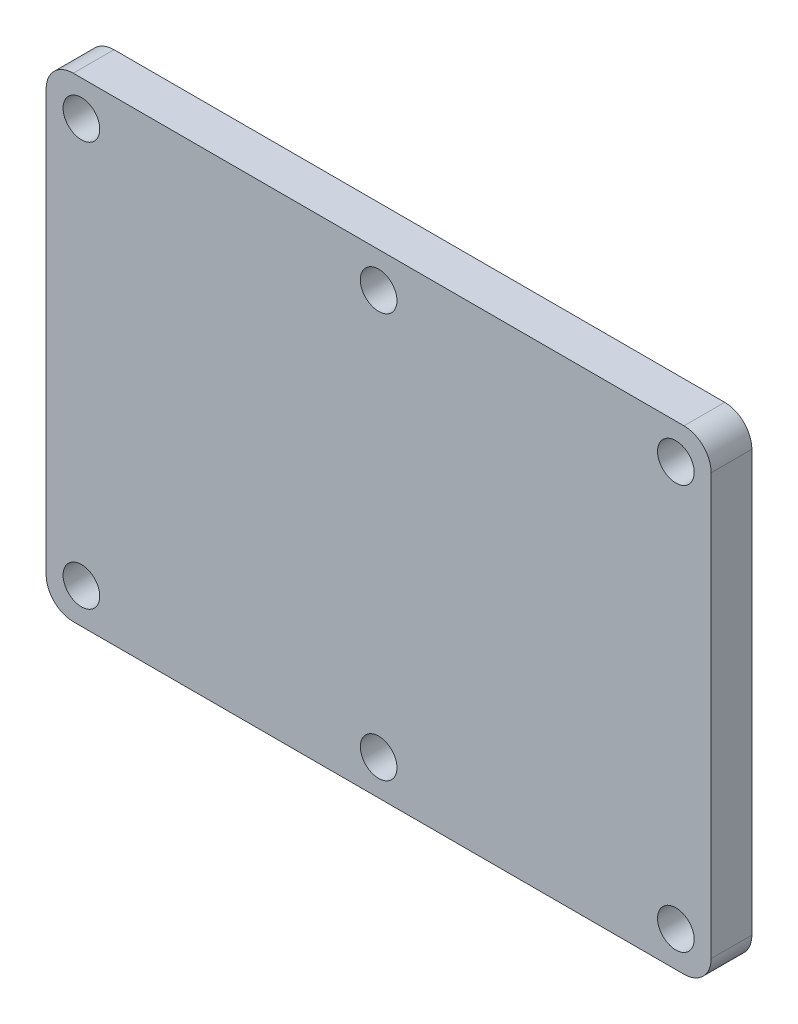
SolidWorks part; units mm, degrees
ref_plane "Plano frontal" through (0, 0, 0) normal (0, 0, 1) x (1, 0, 0)
ref_plane "Plano superior" through (0, 0, 0) normal (0, 1, 0) x (1, 0, 0)
ref_plane "Plano direito" through (0, 0, 0) normal (1, 0, 0) x (0, 0, -1)
sketch "Esboço1" plane through (0, 0, 0) normal (0, 0, 1) x (1, 0, 0)
  line L1 (-24.5, 17.5) -> (24.5, 17.5)
  line L2 (-24.5, 17.5) -> (-24.5, -17.5)
  line L3 (-24.5, -17.5) -> (24.5, -17.5)
  line L4 (24.5, 17.5) -> (24.5, -17.5)
  line L5 (-24.5, 17.5) -> (24.5, -17.5) construction
  line L6 (-24.5, -17.5) -> (24.5, 17.5) construction
  point P0 (0, 0)
  dimension "D1" = 49
  dimension "D2" = 35
extrude "Ressalto-extrusão1" add sketch "Esboço1" along normal blind 3
sketch "Esboço2" plane through (0, 0, 0) normal (0, 0, -1) x (-1, 0, 0)
  line L0 (-24.5, -17.5) -> (-24.5, 17.5) construction
  line L1 (24.5, -17.5) -> (-24.5, -17.5) construction
  line L2 (24.5, 17.5) -> (24.5, -17.5) construction
  circle A0 centre (-21.9, -14.9) radius 1.35
  circle A1 centre (0, -14.9) radius 1.35
  circle A2 centre (21.9, -14.9) radius 1.35
  dimension "D1" = 2.7
  dimension "D2" = 2.6
  dimension "D5" = 2.6
  dimension "D3" = 2.6
  dimension "D4" = 24.5
  dimension "D6" = 2.6
  dimension "D7" = 2.6
extrude "Corte-extrusão1" cut sketch "Esboço2" against normal through all
sketch "Esboço3" plane through (0, 0, 0) normal (0, 0, -1) x (-1, 0, 0)
  line L0 (24.5, 17.5) -> (24.5, -17.5) construction
  line L1 (-24.5, 17.5) -> (24.5, 17.5)
  line L2 (-24.5, 17.5) -> (-24.5, 14.5)
  line L3 (-24.5, 14.5) -> (24.5, 14.5)
  line L4 (24.5, 17.5) -> (24.5, 14.5)
  dimension "D1" = 3
extrude "Ressalto-extrusão3" add sketch "Esboço3" along normal blind 8
sketch "Esboço4" plane through (0, 17.5, 0) normal (0, 1, 0) x (1, 0, 0)
  line L0 (-24.5, -3) -> (-24.5, 8) construction
  line L1 (-24.5, 8) -> (24.5, 8) construction
  line L2 (24.5, -3) -> (24.5, 8) construction
  circle A0 centre (-21.9, 5.4) radius 1.35
  circle A1 centre (0, 5.4) radius 1.35
  circle A2 centre (21.9, 5.4) radius 1.35
  dimension "D1" = 2.7
  dimension "D2" = 2.6
  dimension "D3" = 2.6
  dimension "D4" = 2.6
  dimension "D5" = 2.6
  dimension "D6" = 2.6
  dimension "D7" = 24.5
extrude "Corte-extrusão2" cut sketch "Esboço4" against normal through all
fillet "Filete1" radius 2 2 edges at (24.5, -17.5, 1.5) (-24.5, -17.5, 1.5)
fillet "Filete2" radius 2 2 edges at (-24.5, 16, -8) (24.5, 16, -8)
sketch "Esboço5" plane through (0, 14.5, 0) normal (0, -1, 0) x (-1, 0, 0)
  line L0 (24.5, 0) -> (24.5, 8)
  line L2 (22.5, 8) -> (24.5, 8)
  line L3 (22.5, 8) -> (-24.5, 8)
  line L4 (-24.5, 0) -> (-24.5, 8)
  line L5 (24.5, 0) -> (-24.5, 0)
extrude "Corte-extrusão3" cut sketch "Esboço5" against normal blind 10
fillet "Filete3" radius 2 2 edges at (24.5, 17.5, 1.5) (-24.5, 17.5, 1.5)
sketch "Esboço6" plane through (0, 0, 3) normal (0, 0, 1) x (1, 0, 0)
  line L0 (24.5, -15.5) -> (24.5, 15.5) construction
  line L1 (22.5, 17.5) -> (-22.5, 17.5) construction
  line L2 (-24.5, 15.5) -> (-24.5, -15.5) construction
  circle A0 centre (21.9, 14.9) radius 1.35
  circle A1 centre (0, 14.9) radius 1.35
  circle A2 centre (-21.9, 14.9) radius 1.35
  dimension "D3" = 2.7
  dimension "D5" = 2.7
  dimension "D9" = 2.7
  dimension "D1" = 2.6
  dimension "D2" = 2.6
  dimension "D4" = 24.5
  dimension "D6" = 2.6
  dimension "D7" = 2.6
  dimension "D8" = 2.6
extrude "Corte-extrusão4" cut sketch "Esboço6" against normal through all
